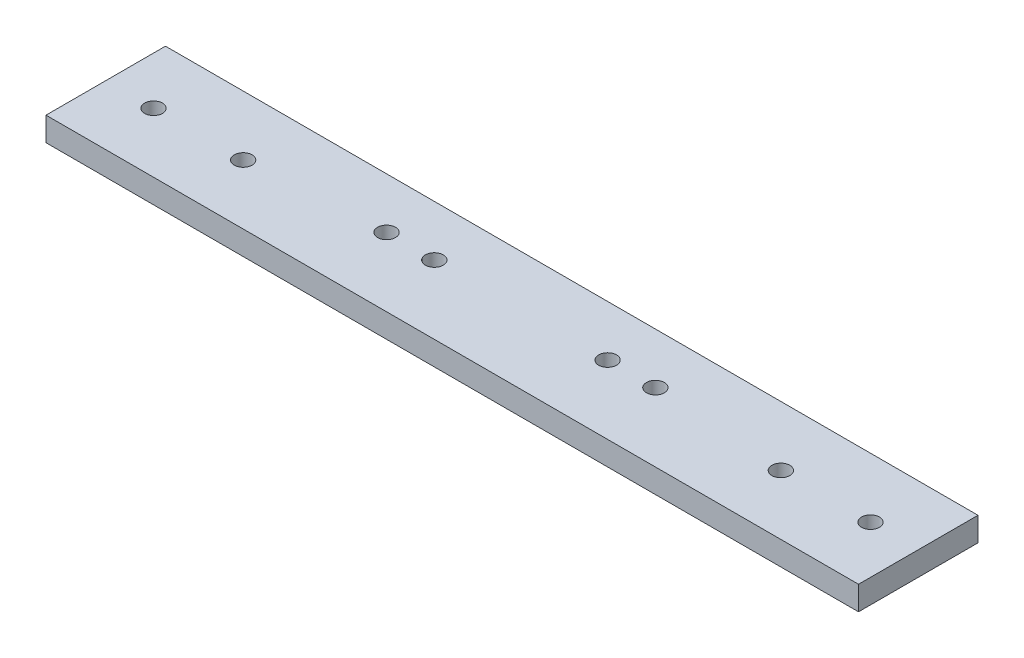
SolidWorks part; units mm, degrees
ref_plane "Front Plane" through (0, 0, 0) normal (0, 0, 1) x (1, 0, 0)
ref_plane "Top Plane" through (0, 0, 0) normal (0, 1, 0) x (1, 0, 0)
ref_plane "Right Plane" through (0, 0, 0) normal (1, 0, 0) x (0, 0, -1)
sketch "Sketch1" plane through (0, 0, 0) normal (0, 1, 0) x (1, 0, 0)
  line L0 (0, 0) -> (0, -14.4865) construction
  line L1 (-68, 10) -> (68, 10)
  line L2 (-68, 10) -> (-68, -10)
  line L3 (-68, -10) -> (68, -10)
  line L4 (68, 10) -> (68, -10)
  line L5 (-68, 10) -> (68, -10) construction
  line L6 (-68, -10) -> (68, 10) construction
  circle A1 centre (22.5, 1.5) radius 1.5
  circle A2 centre (14.5, 1.5) radius 1.5
  circle A3 centre (-14.5, 1.5) radius 1.5
  circle A4 centre (-22.5, 1.5) radius 1.5
  circle A5 centre (60, 0) radius 1.5
  circle A6 centre (45, 0) radius 1.5
  circle A7 centre (-45, 0) radius 1.5
  circle A8 centre (-60, 0) radius 1.5
  point P0 (0, 0)
  dimension "D3" = 45.5
  dimension "D4" = 11.5
  dimension "D5" = 3
  dimension "D7" = 8
  dimension "D8" = 3
  dimension "D9" = 8
  dimension "D10" = 10
  dimension "D12" = 15
  dimension "D1" = 136
  dimension "D2" = 20
  dimension "D11" = 2
  dimension "D6" = 2
extrude "Boss-Extrude1" add sketch "Sketch1" along normal blind 4
